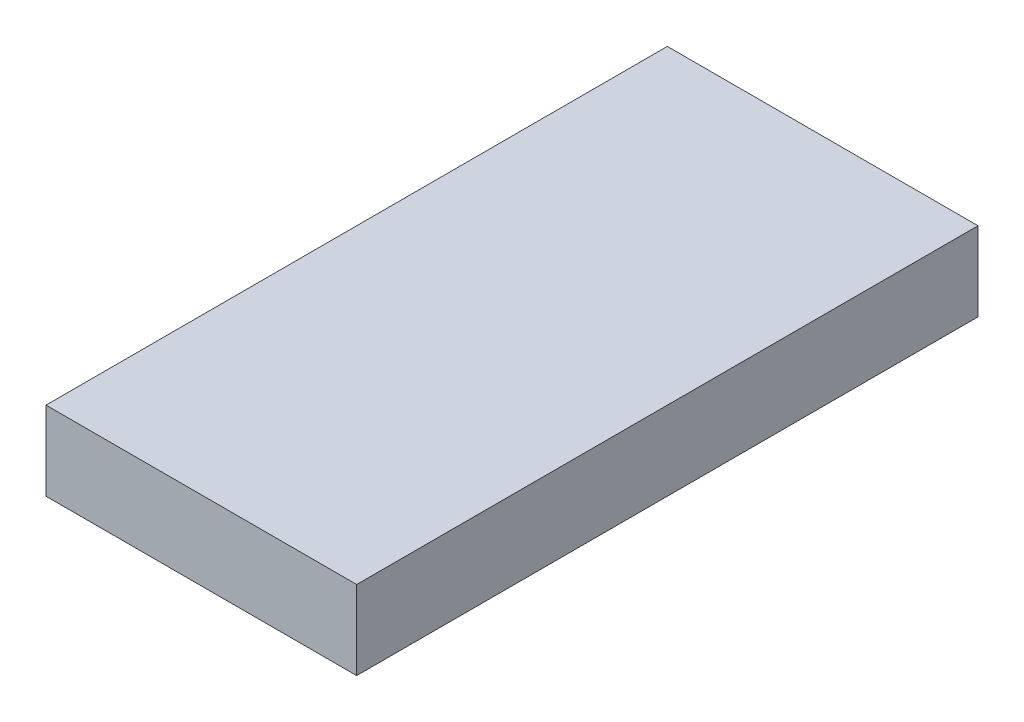
SolidWorks part; units mm, degrees
ref_plane "Front Plane" through (0, 0, 0) normal (0, 0, 1) x (1, 0, 0)
ref_plane "Top Plane" through (0, 0, 0) normal (0, 1, 0) x (1, 0, 0)
ref_plane "Right Plane" through (0, 0, 0) normal (1, 0, 0) x (0, 0, -1)
sketch "Sketch1" plane through (0, 0, 0) normal (0, 1, 0) x (1, 0, 0)
  line L1 (0, 0) -> (25, 0)
  line L2 (0, 0) -> (0, -50)
  line L3 (0, -50) -> (25, -50)
  line L4 (25, 0) -> (25, -50)
  dimension "D1" = 50
  dimension "D2" = 25
extrude "Boss-Extrude1" add sketch "Sketch1" along normal blind 6.35
sketch "Sketch2" plane through (0, 6.35, 0) normal (0, 1, 0) x (1, 0, 0)
  line L0 (25, -25) -> (0, -25) construction
  line L1 (25, -50) -> (25, 0) construction
  line L2 (0, 0) -> (0, -50) construction
  line L3 (12.5, 0) -> (12.5, -50) construction
  line L4 (25, 0) -> (0, 0) construction
  line L5 (0, -50) -> (25, -50) construction
  point P12 (12.5, -10)
  point P15 (12.5, -60)
  point P16 (0, 0)
  point P17 (0, 0)
  dimension "D1" = 15
hole_wizard "CBORE for 1/4 Button Head Cap Screw1" positions "Sketch3" profile "Sketch4" counterbore size "1/4" standard "ANSI Inch"
sketch "Sketch3" plane through (0, 6.35, 0) normal (0, 1, 0) x (1, 0, 0)
  point P0 (12.5, 50)
  point P3 (12.5, -60)
sketch "Sketch4" plane through (12.5, 6.35, -50) normal (1, 0, 0) x (0, 0, 1)
  line L0 (0, 0) -> (0, 6.35)
  line L1 (0, 6.35) -> (3.5712, 6.35)
  line L3 (3.5712, 6.35) -> (3.5712, 3.3528)
  line L4 (3.5712, 3.3528) -> (5.9538, 3.3528)
  line L5 (5.9538, 3.3528) -> (5.9538, 0)
  line L7 (5.9538, 0) -> (0, 0)
  line L11 (0, -6.35) -> (0, 107.95) construction
  dimension "Thru Hole Dia." = 7.1425
  dimension "Thru Hole Depth" = 6.35
  dimension "C'Bore Dia." = 11.9075
  dimension "C'Bore Depth" = 3.3528
